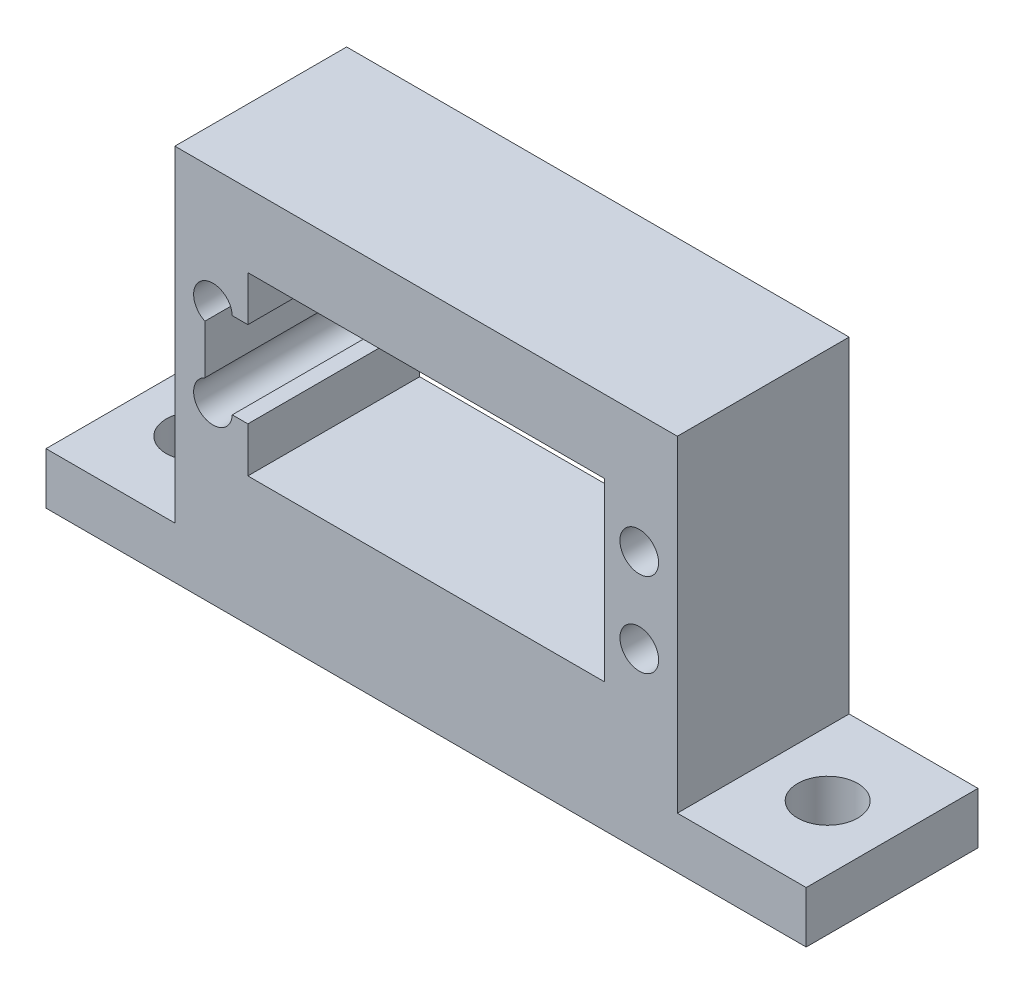
SolidWorks part; units mm, degrees
ref_plane "Front Plane" through (0, 0, 0) normal (0, 0, 1) x (1, 0, 0)
ref_plane "Top Plane" through (0, 0, 0) normal (0, 1, 0) x (1, 0, 0)
ref_plane "Right Plane" through (0, 0, 0) normal (1, 0, 0) x (0, 0, -1)
sketch "Sketch1" plane through (0, 0, 0) normal (0, 0, 1) x (1, 0, 0)
  line L0 (-44.25, 0) -> (44.25, 0)
  line L1 (44.25, 0) -> (44.25, 6)
  line L2 (44.25, 6) -> (29.25, 6)
  line L3 (29.25, 6) -> (29.25, 44)
  line L4 (29.25, 44) -> (-29.25, 44)
  line L5 (0, 0) -> (0, 132.122) construction
  line L6 (-20.75, 35.5) -> (20.75, 35.5)
  line L7 (20.75, 35.5) -> (20.75, 15)
  line L8 (20.75, 15) -> (-20.75, 15)
  line L10 (-29.25, 6) -> (-29.25, 44)
  line L11 (-44.25, 6) -> (-29.25, 6)
  line L12 (-44.25, 0) -> (-44.25, 6)
  line L13 (-20.75, 30.25) -> (-22.5672, 30.25)
  line L14 (-25.75, 28.1035) -> (-25.75, 22.3965)
  line L15 (-22.5672, 20.25) -> (-20.75, 20.25)
  line L16 (-20.75, 35.5) -> (-20.75, 30.25)
  line L18 (-20.75, 20.25) -> (-20.75, 15)
  line L19 (27.065, 11.4349) -> (27.065, 38.773) construction
  line L20 (20.75, 25.25) -> (36.6589, 25.25) construction
  circle A0 centre (24.815, 30.15) radius 2.25
  circle A1 centre (24.815, 20.35) radius 2.25
  arc A2 (-25.75, 22.3965) -> (-22.5672, 20.25) centre (-24.815, 20.35) ccw
  arc A3 (-25.75, 28.1035) -> (-22.5672, 30.25) centre (-24.815, 30.15) cw
  point P15 (-25.75, 25.25)
  point P18 (0, 15)
  point P19 (0, 35.5)
  point P20 (0, 44)
  dimension "D11" = 4.5
  dimension "D1" = 41.5
  dimension "D2" = 20.5
  dimension "D3" = 15
  dimension "D4" = 8.5
  dimension "D5" = 15
  dimension "D6" = 8.5
  dimension "D7" = 6
  dimension "D8" = 10
  dimension "D9" = 5
  dimension "D10" = 54.13
  dimension "D12" = 4.9
  dimension "D13" = 5
extrude "Boss-Extrude1" add sketch "Sketch1" along normal blind 20
sketch "Sketch2" plane through (0, 6, 0) normal (0, 1, 0) x (1, 0, 0)
  line L0 (44.25, -10) -> (-44.25, -10) construction
  line L1 (44.25, -20) -> (44.25, 0) construction
  line L2 (-44.25, -20) -> (-44.25, 0) construction
  line L3 (36.75, 0) -> (36.75, -20) construction
  line L4 (44.25, 0) -> (29.25, 0) construction
  line L5 (44.25, -20) -> (29.25, -20) construction
  line L6 (0, 0) -> (0, -20) construction
  line L7 (29.25, 0) -> (-29.25, 0) construction
  line L8 (29.25, -20) -> (-29.25, -20) construction
  circle A0 centre (36.75, -10) radius 3.5
  circle A1 centre (-36.75, -10) radius 3.5
  dimension "D1" = 7
extrude "Cut-Extrude1" cut sketch "Sketch2" against normal through all
